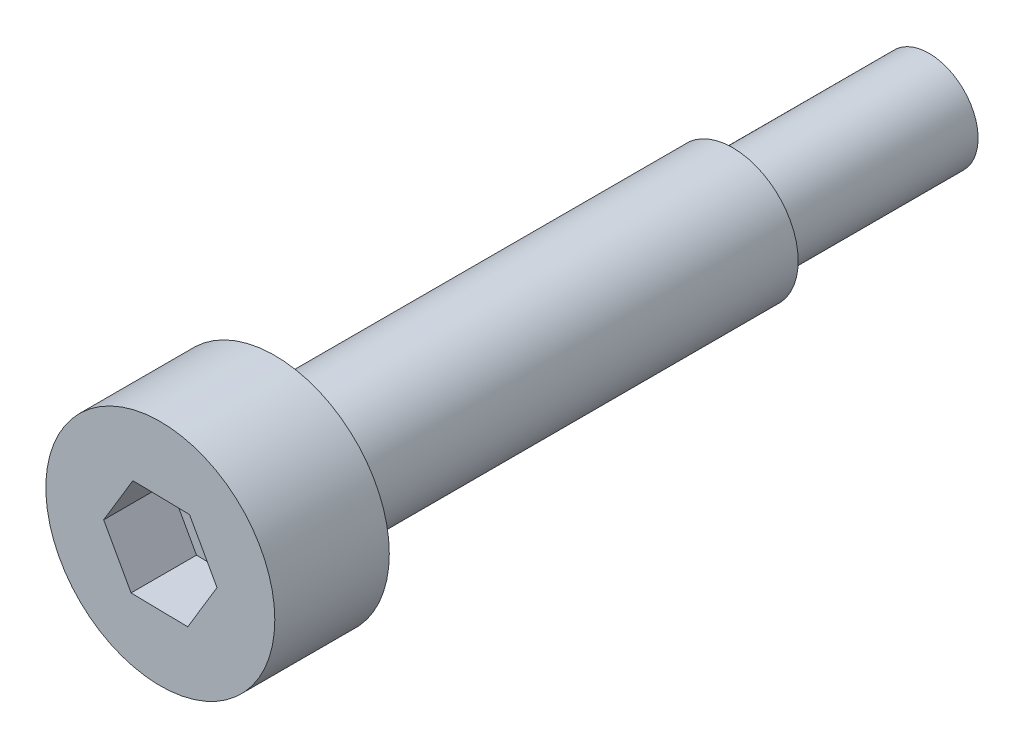
SolidWorks part; units mm, degrees
material "不锈钢 (铁素体)"
ref_plane "前视基准面" through (0, 0, 0) normal (0, 0, 1) x (1, 0, 0)
ref_plane "上视基准面" through (0, 0, 0) normal (0, 1, 0) x (1, 0, 0)
ref_plane "右视基准面" through (0, 0, 0) normal (1, 0, 0) x (0, 0, -1)
sketch "草图1" plane through (0, 0, 0) normal (0, 0, 1) x (1, 0, 0)
  circle A0 centre (0, 0) radius 3.5
  dimension "D1" = 7
extrude "凸台-拉伸1" add sketch "草图1" along normal blind 3.5
sketch "草图2" plane through (0, 0, 3.5) normal (0, 0, 1) x (1, 0, 0)
  line L1 (0.8936, 1.4837) -> (-0.8381, 1.5158)
  line L2 (-0.8381, 1.5158) -> (-1.7318, 0.0321)
  line L3 (-1.7318, 0.0321) -> (-0.8936, -1.4837)
  line L4 (-0.8936, -1.4837) -> (0.8381, -1.5158)
  line L5 (0.8381, -1.5158) -> (1.7318, -0.0321)
  line L6 (1.7318, -0.0321) -> (0.8936, 1.4837)
  circle A0 centre (0, 0) radius 1.5 construction
  dimension "D1" = 3
extrude "切除-拉伸1" cut sketch "草图2" against normal blind 2
sketch "草图3" plane through (0, 0, 0) normal (0, 0, -1) x (-1, 0, 0)
  circle A0 centre (0, 0) radius 2
  dimension "D1" = 4
extrude "凸台-拉伸2" add sketch "草图3" along normal blind 14
sketch "草图4" plane through (0, 0, -14) normal (0, 0, -1) x (-1, 0, 0)
  circle A0 centre (0, 0) radius 1.5
  dimension "D1" = 3
extrude "凸台-拉伸3" add sketch "草图4" along normal blind 6
cosmetic thread "装饰螺纹线1" parameters "D2"=2
